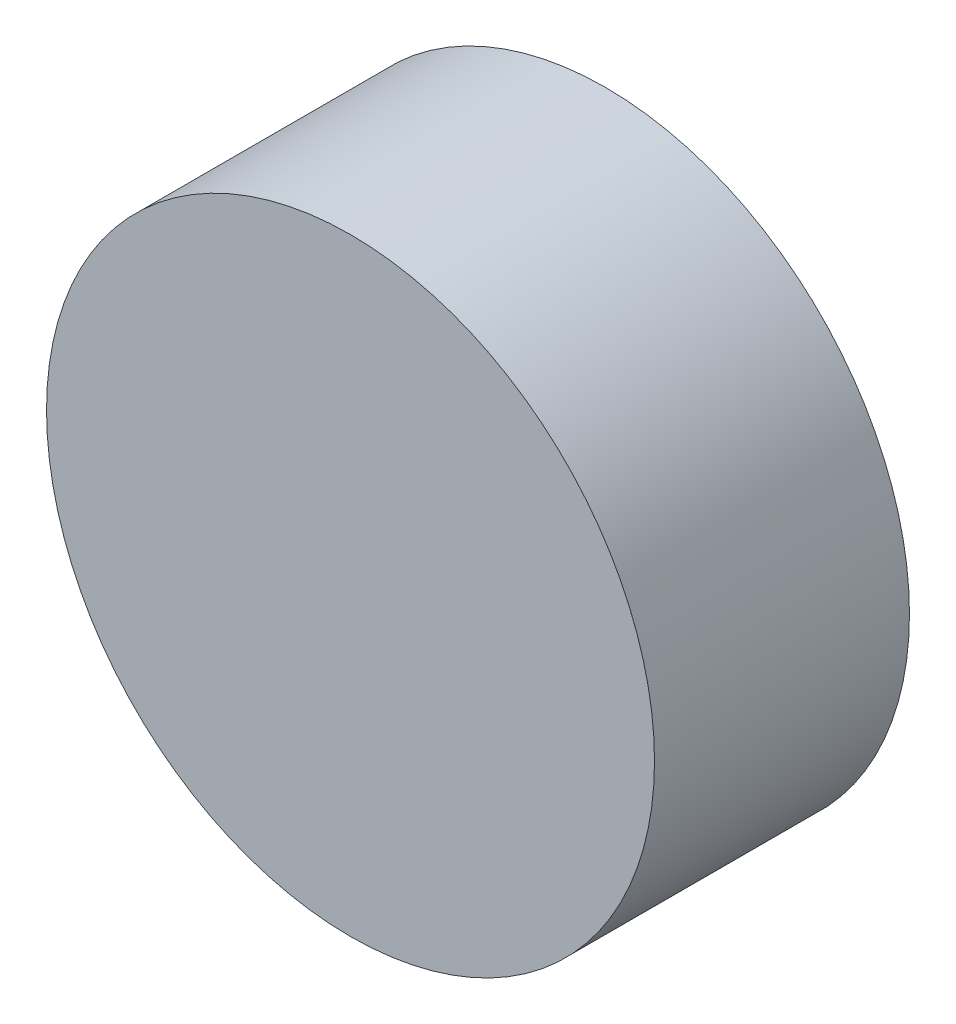
SolidWorks part; units mm, degrees
ref_plane "Alzado" through (0, 0, 0) normal (0, 0, 1) x (1, 0, 0)
ref_plane "Planta" through (0, 0, 0) normal (0, 1, 0) x (1, 0, 0)
ref_plane "Vista lateral" through (0, 0, 0) normal (1, 0, 0) x (0, 0, -1)
sketch "Croquis1" plane through (0, 0, 0) normal (0, 0, 1) x (1, 0, 0)
  circle A0 centre (0, 0) radius 31
  dimension "D1" = 62
extrude "Saliente-Extruir1" add sketch "Croquis1" along normal blind 26
